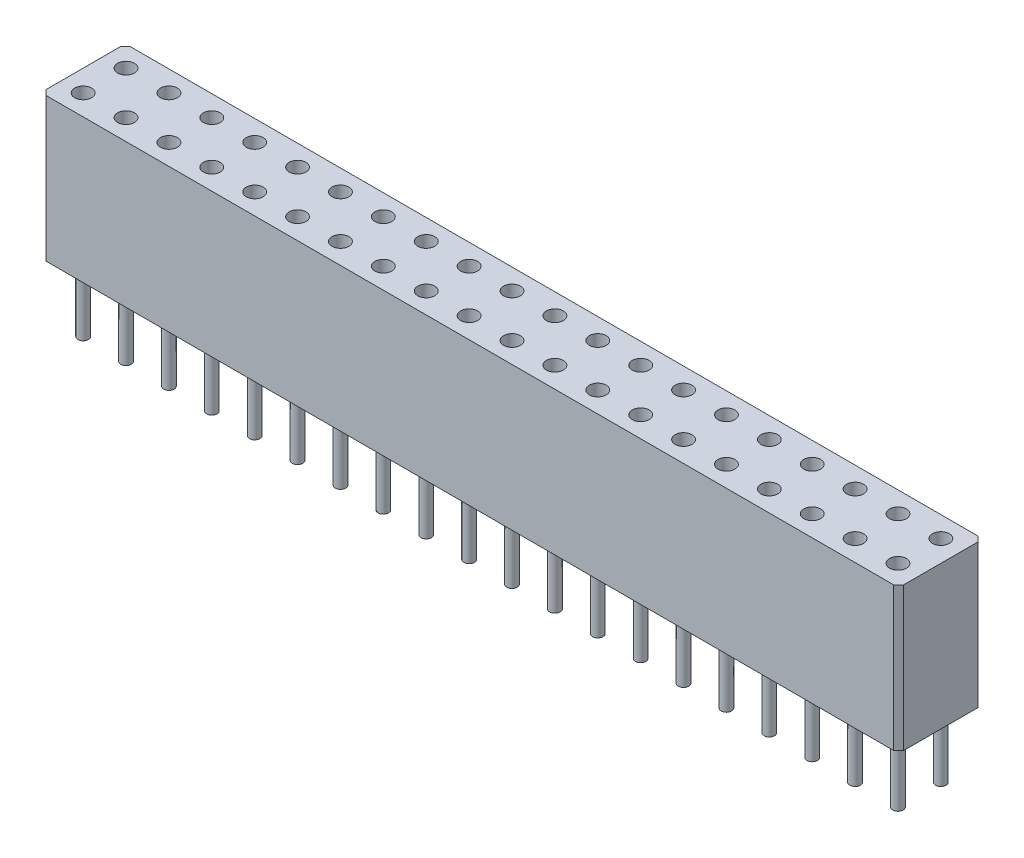
SolidWorks part; units mm, degrees
ref_plane "Спереди" through (0, 0, 0) normal (0, 0, 1) x (1, 0, 0)
ref_plane "Сверху" through (0, 0, 0) normal (0, 1, 0) x (1, 0, 0)
ref_plane "Справа" through (0, 0, 0) normal (1, 0, 0) x (0, 0, -1)
sketch "Эскиз2" plane through (0, 0, 0) normal (0, 1, 0) x (1, 0, 0)
  line L0 (49.4117, 15.0437) -> (86.9117, 15.0437)
  line L2 (49.4117, 10.0437) -> (86.9117, 10.0437)
  line L3 (36.7117, 10.0437) -> (49.4117, 10.0437)
  line L4 (36.7117, 15.0437) -> (49.4117, 15.0437)
  line L17 (36.4117, 14.7437) -> (36.4117, 10.3437)
  line L18 (36.7117, 10.0437) -> (36.4117, 10.3437)
  line L19 (36.7117, 15.0437) -> (36.4117, 14.7437)
  line L112 (87.2117, 14.7437) -> (87.2117, 10.3437)
  line L113 (86.9117, 10.0437) -> (87.2117, 10.3437)
  line L117 (86.9117, 15.0437) -> (87.2117, 14.7437)
  circle A0 centre (83.4017, 11.2737) radius 0.31
  circle A1 centre (80.8617, 11.2737) radius 0.31
  circle A2 centre (78.3217, 11.2737) radius 0.31
  circle A3 centre (75.7817, 11.2737) radius 0.31
  circle A4 centre (73.2417, 11.2737) radius 0.31
  circle A5 centre (70.7017, 11.2737) radius 0.31
  circle A6 centre (68.1617, 11.2737) radius 0.31
  circle A7 centre (65.6217, 11.2737) radius 0.31
  circle A8 centre (63.0817, 11.2737) radius 0.31
  circle A9 centre (60.5417, 11.2737) radius 0.31
  circle A10 centre (58.0017, 11.2737) radius 0.31
  circle A11 centre (55.4617, 11.2737) radius 0.31
  circle A12 centre (52.9217, 11.2737) radius 0.31
  circle A13 centre (50.3817, 11.2737) radius 0.31
  circle A14 centre (47.8417, 11.2737) radius 0.31
  circle A15 centre (45.3017, 11.2737) radius 0.31
  circle A16 centre (42.7617, 11.2737) radius 0.31
  circle A17 centre (40.2217, 11.2737) radius 0.31
  circle A18 centre (37.6817, 11.2737) radius 0.31
  circle A19 centre (83.4017, 13.8137) radius 0.31
  circle A20 centre (80.8617, 13.8137) radius 0.31
  circle A21 centre (78.3217, 13.8137) radius 0.31
  circle A22 centre (75.7817, 13.8137) radius 0.31
  circle A23 centre (73.2417, 13.8137) radius 0.31
  circle A24 centre (70.7017, 13.8137) radius 0.31
  circle A25 centre (68.1617, 13.8137) radius 0.31
  circle A26 centre (65.6217, 13.8137) radius 0.31
  circle A27 centre (63.0817, 13.8137) radius 0.31
  circle A28 centre (60.5417, 13.8137) radius 0.31
  circle A29 centre (85.9417, 11.2737) radius 0.31
  circle A30 centre (58.0017, 13.8137) radius 0.31
  circle A31 centre (55.4617, 13.8137) radius 0.31
  circle A32 centre (52.9217, 13.8137) radius 0.31
  circle A33 centre (50.3817, 13.8137) radius 0.31
  circle A34 centre (47.8417, 13.8137) radius 0.31
  circle A35 centre (45.3017, 13.8137) radius 0.31
  circle A36 centre (42.7617, 13.8137) radius 0.31
  circle A37 centre (40.2217, 13.8137) radius 0.31
  circle A38 centre (37.6817, 13.8137) radius 0.31
  circle A39 centre (85.9417, 13.8137) radius 0.31
  point P13 (54.5411, 14.8708)
  point P174 (57.0811, 14.8708)
extrude "Бобышка-Вытянуть4" add sketch "Эскиз2" against normal blind 8.5
sketch "Эскиз7" plane through (0, 0, 0) normal (0, 1, 0) x (1, 0, 0)
  circle A0 centre (83.4017, 11.2737) radius 0.5
  circle A1 centre (80.8617, 11.2737) radius 0.5
  circle A2 centre (78.3217, 11.2737) radius 0.5
  circle A3 centre (75.7817, 11.2737) radius 0.5
  circle A4 centre (73.2417, 11.2737) radius 0.5
  circle A5 centre (70.7017, 11.2737) radius 0.5
  circle A6 centre (68.1617, 11.2737) radius 0.5
  circle A7 centre (65.6217, 11.2737) radius 0.5
  circle A8 centre (63.0817, 11.2737) radius 0.5
  circle A9 centre (60.5417, 11.2737) radius 0.5
  circle A10 centre (58.0017, 11.2737) radius 0.5
  circle A11 centre (55.4617, 11.2737) radius 0.5
  circle A12 centre (52.9217, 11.2737) radius 0.5
  circle A13 centre (50.3817, 11.2737) radius 0.5
  circle A14 centre (47.8417, 11.2737) radius 0.5
  circle A15 centre (45.3017, 11.2737) radius 0.5
  circle A16 centre (42.7617, 11.2737) radius 0.5
  circle A17 centre (40.2217, 11.2737) radius 0.5
  circle A18 centre (37.6817, 11.2737) radius 0.5
  circle A19 centre (83.4017, 13.8137) radius 0.5
  circle A20 centre (80.8617, 13.8137) radius 0.5
  circle A21 centre (78.3217, 13.8137) radius 0.5
  circle A22 centre (75.7817, 13.8137) radius 0.5
  circle A23 centre (73.2417, 13.8137) radius 0.5
  circle A24 centre (70.7017, 13.8137) radius 0.5
  circle A25 centre (68.1617, 13.8137) radius 0.5
  circle A26 centre (65.6217, 13.8137) radius 0.5
  circle A27 centre (63.0817, 13.8137) radius 0.5
  circle A28 centre (60.5417, 13.8137) radius 0.5
  circle A29 centre (85.9417, 11.2737) radius 0.5
  circle A58 centre (58.0017, 13.8137) radius 0.5
  circle A59 centre (55.4617, 13.8137) radius 0.5
  circle A60 centre (52.9217, 13.8137) radius 0.5
  circle A61 centre (50.3817, 13.8137) radius 0.5
  circle A62 centre (47.8417, 13.8137) radius 0.5
  circle A63 centre (45.3017, 13.8137) radius 0.5
  circle A64 centre (42.7617, 13.8137) radius 0.5
  circle A65 centre (40.2217, 13.8137) radius 0.5
  circle A66 centre (37.6817, 13.8137) radius 0.5
  circle A67 centre (85.9417, 13.8137) radius 0.5
extrude "Вырез-Вытянуть1" cut sketch "Эскиз7" against normal blind 8
sketch "Эскиз8" plane through (0, -8.5, 0) normal (0, -1, 0) x (1, 0, 0)
  circle A0 centre (37.6817, -11.2737) radius 0.31
  circle A1 centre (40.2217, -11.2737) radius 0.31
  circle A2 centre (42.7617, -11.2737) radius 0.31
  circle A3 centre (45.3017, -11.2737) radius 0.31
  circle A4 centre (47.8417, -11.2737) radius 0.31
  circle A5 centre (50.3817, -11.2737) radius 0.31
  circle A6 centre (52.9217, -11.2737) radius 0.31
  circle A7 centre (55.4617, -11.2737) radius 0.31
  circle A8 centre (58.0017, -11.2737) radius 0.31
  circle A9 centre (60.5417, -11.2737) radius 0.31
  circle A10 centre (63.0817, -11.2737) radius 0.31
  circle A11 centre (65.6217, -11.2737) radius 0.31
  circle A12 centre (68.1617, -11.2737) radius 0.31
  circle A13 centre (70.7017, -11.2737) radius 0.31
  circle A14 centre (73.2417, -11.2737) radius 0.31
  circle A15 centre (75.7817, -11.2737) radius 0.31
  circle A16 centre (78.3217, -11.2737) radius 0.31
  circle A17 centre (80.8617, -11.2737) radius 0.31
  circle A18 centre (83.4017, -11.2737) radius 0.31
  circle A19 centre (85.9417, -11.2737) radius 0.31
  circle A20 centre (40.2217, -13.8137) radius 0.31
  circle A21 centre (42.7617, -13.8137) radius 0.31
  circle A22 centre (45.3017, -13.8137) radius 0.31
  circle A23 centre (47.8417, -13.8137) radius 0.31
  circle A24 centre (50.3817, -13.8137) radius 0.31
  circle A25 centre (52.9217, -13.8137) radius 0.31
  circle A26 centre (55.4617, -13.8137) radius 0.31
  circle A27 centre (58.0017, -13.8137) radius 0.31
  circle A28 centre (60.5417, -13.8137) radius 0.31
  circle A29 centre (63.0817, -13.8137) radius 0.31
  circle A30 centre (65.6217, -13.8137) radius 0.31
  circle A31 centre (68.1617, -13.8137) radius 0.31
  circle A32 centre (70.7017, -13.8137) radius 0.31
  circle A33 centre (73.2417, -13.8137) radius 0.31
  circle A34 centre (75.7817, -13.8137) radius 0.31
  circle A35 centre (78.3217, -13.8137) radius 0.31
  circle A36 centre (80.8617, -13.8137) radius 0.31
  circle A37 centre (83.4017, -13.8137) radius 0.31
  circle A38 centre (85.9417, -13.8137) radius 0.31
  circle A39 centre (37.6817, -13.8137) radius 0.31
extrude "Бобышка-Вытянуть5" add sketch "Эскиз8" along normal blind 4 separate body
